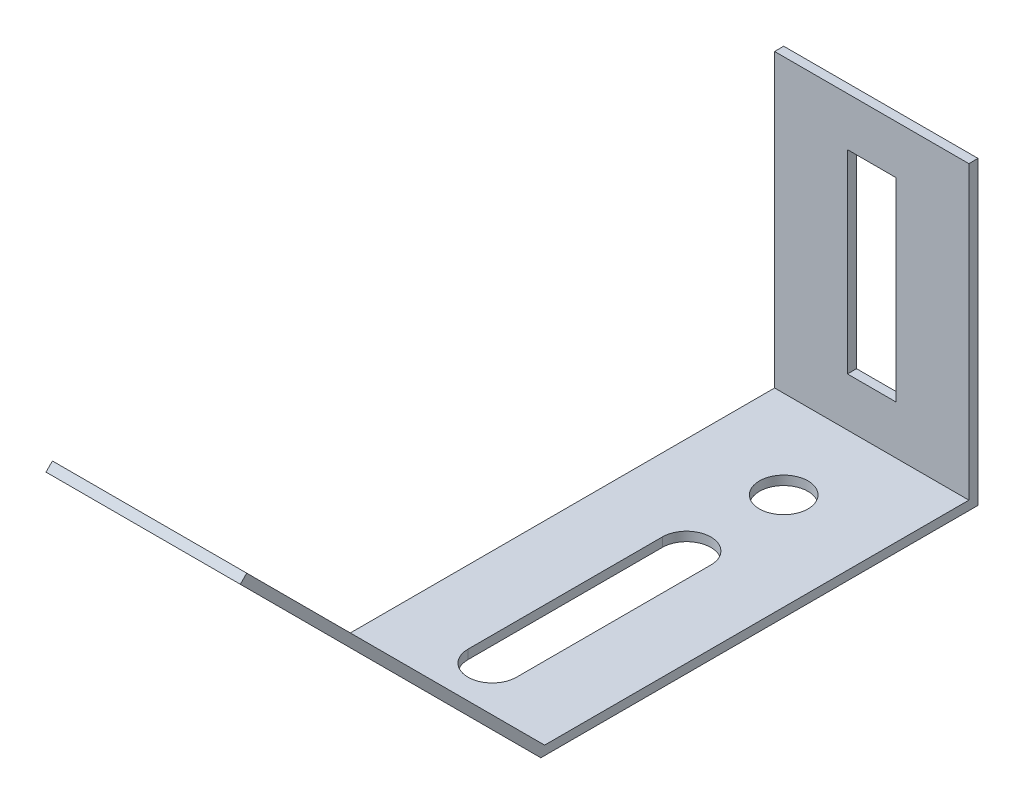
SolidWorks part; units mm, degrees
ref_plane "Front Plane" through (0, 0, 0) normal (0, 0, 1) x (1, 0, 0)
ref_plane "Top Plane" through (0, 0, 0) normal (0, 1, 0) x (1, 0, 0)
ref_plane "Right Plane" through (0, 0, 0) normal (1, 0, 0) x (0, 0, -1)
sketch "Sketch1" plane through (0, 0, 0) normal (0, 1, 0) x (1, 0, 0)
  line L0 (0, -14.2875) -> (0, 14.2875) construction
  line L1 (-6.35, -14.2875) -> (6.35, -14.2875)
  line L2 (-6.35, -14.2875) -> (-6.35, 14.2875)
  line L3 (-6.35, 14.2875) -> (6.35, 14.2875)
  line L4 (6.35, -14.2875) -> (6.35, 14.2875)
  line L5 (-6.35, -14.2875) -> (6.35, 14.2875) construction
  line L6 (-6.35, 14.2875) -> (6.35, -14.2875) construction
  line L7 (0, 1.5875) -> (0, -11.1125) construction
  line L8 (1.5875, 1.5875) -> (1.5875, -11.1125)
  line L9 (-1.5875, 1.5875) -> (-1.5875, -11.1125)
  circle A0 centre (0, 7.9375) radius 1.5875
  arc A1 (1.5875, 1.5875) -> (-1.5875, 1.5875) centre (0, 1.5875) ccw
  arc A2 (-1.5875, -11.1125) -> (1.5875, -11.1125) centre (0, -11.1125) ccw
  point P0 (0, 0)
  point P12 (0, -4.7625)
  point P17 (1.5875, 2.9276)
  point P18 (0, 3.175)
  point P19 (0, -12.7)
  point P20 (1.5875, 2.11)
  dimension "D4" = 3.175
  dimension "D1" = 28.575
  dimension "D2" = 12.7
  dimension "D3" = 6.35
  dimension "D5" = 15.875
  dimension "D6" = 4.7625
extrude "Boss-Extrude1" add sketch "Sketch1" along normal blind 0.5953
sketch "Sketch3" plane through (0, 0, -14.2875) normal (0, 0, -1) x (-1, 0, 0)
  line L0 (6.35, 0.5953) -> (6.35, 0) construction
  line L1 (-6.35, 0.5953) -> (6.35, 0.5953)
  line L2 (-6.35, 0.5953) -> (-6.35, 19.6453)
  line L3 (-6.35, 19.6453) -> (6.35, 19.6453)
  line L4 (6.35, 0.5953) -> (6.35, 19.6453)
  line L5 (0, 0) -> (0, 19.6453) construction
  line L6 (1.5875, 16.4703) -> (-1.5875, 16.4703)
  line L7 (1.5875, 16.4703) -> (1.5875, 3.7703)
  line L8 (1.5875, 3.7703) -> (-1.5875, 3.7703)
  line L9 (-1.5875, 16.4703) -> (-1.5875, 3.7703)
  line L10 (-6.35, 0) -> (6.35, 0) construction
  dimension "D1" = 19.05
  dimension "D2" = 12.7
  dimension "D3" = 3.175
  dimension "D4" = 3.175
extrude "Boss-Extrude2" add sketch "Sketch3" against normal blind 0.5953
sketch "Sketch4" plane through (6.35, 0, 0) normal (1, 0, 0) x (0, 0, -1)
  line L0 (-14.2875, 0) -> (-33.9328, 19.6453)
  line L1 (-14.2875, 0) -> (14.2875, 0) construction
  line L5 (-14.0409, 0.5953) -> (-33.5119, 20.0663)
  line L6 (-14.2875, 0) -> (-14.2875, 0.5953)
  line L7 (-14.2875, 0.5953) -> (-14.0409, 0.5953)
  line L8 (13.6922, 0.5953) -> (-14.2875, 0.5953) construction
  line L9 (-33.5119, 20.0663) -> (-33.9328, 19.6453)
  line L10 (-13.8666, 0.4209) -> (-33.5119, 20.0663) construction
  dimension "D1" = 45
  dimension "D2" = 0.5953
extrude "Boss-Extrude3" add sketch "Sketch4" against normal up to surface (12.7 mm away) up to face at (-6.35, 6.7469, -4.5641)
